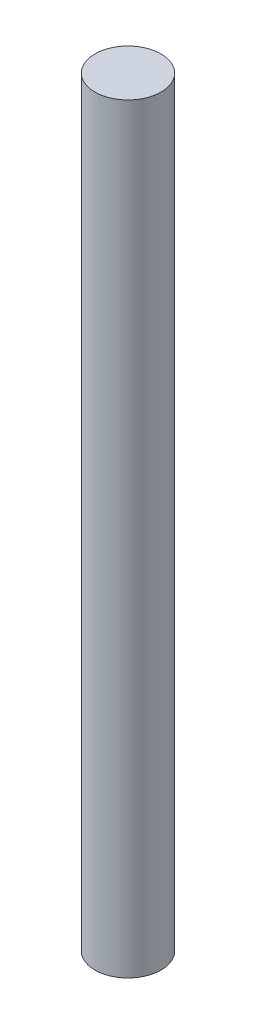
SolidWorks part; units mm, degrees
ref_plane "Front" through (0, 0, 0) normal (0, 0, 1) x (1, 0, 0)
ref_plane "Top" through (0, 0, 0) normal (0, 1, 0) x (1, 0, 0)
ref_plane "Right" through (0, 0, 0) normal (1, 0, 0) x (0, 0, -1)
sketch "Sketch1" plane through (0, 0, 0) normal (0, 1, 0) x (1, 0, 0)
  circle A0 centre (0, 0) radius 6.35
  dimension "D1" = 12.7
extrude "Boss-Extrude1" add sketch "Sketch1" along normal mid plane 146.05 contours A0
